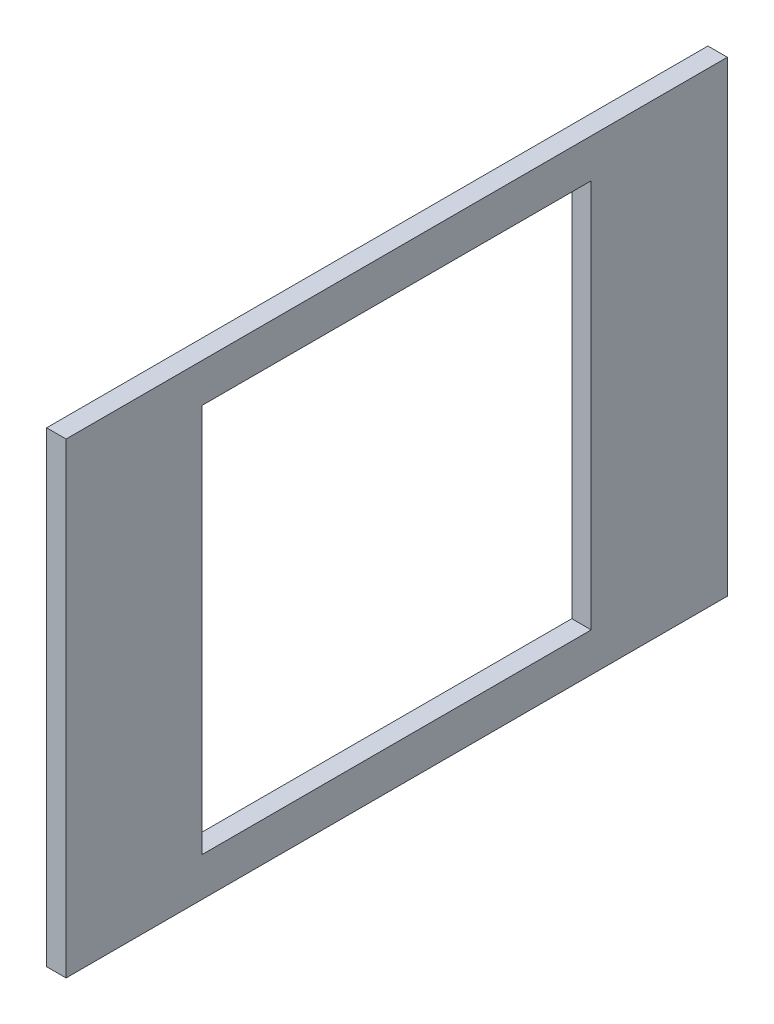
SolidWorks part; units mm, degrees
ref_plane "Front Plane" through (0, 0, 0) normal (0, 0, 1) x (1, 0, 0)
ref_plane "Top Plane" through (0, 0, 0) normal (0, 1, 0) x (1, 0, 0)
ref_plane "Right Plane" through (0, 0, 0) normal (1, 0, 0) x (0, 0, -1)
sketch "Sketch1" plane through (0, 0, 0) normal (1, 0, 0) x (0, 0, -1)
  line L1 (215.9, 152.4) -> (-215.9, 152.4)
  line L2 (215.9, 152.4) -> (215.9, -152.4)
  line L3 (215.9, -152.4) -> (-215.9, -152.4)
  line L4 (-215.9, 152.4) -> (-215.9, -152.4)
  line L5 (215.9, 152.4) -> (-215.9, -152.4) construction
  line L6 (215.9, -152.4) -> (-215.9, 152.4) construction
  line L7 (127, 127) -> (-127, 127)
  line L8 (127, 127) -> (127, -127)
  line L9 (127, -127) -> (-127, -127)
  line L10 (-127, 127) -> (-127, -127)
  line L11 (127, 127) -> (-127, -127) construction
  line L12 (127, -127) -> (-127, 127) construction
  point P0 (0, 0)
  point P6 (0, 0)
  dimension "D1" = 304.8
  dimension "D2" = 431.8
  dimension "D3" = 254
  dimension "D4" = 254
extrude "Boss-Extrude1" add sketch "Sketch1" along normal blind 12.7
